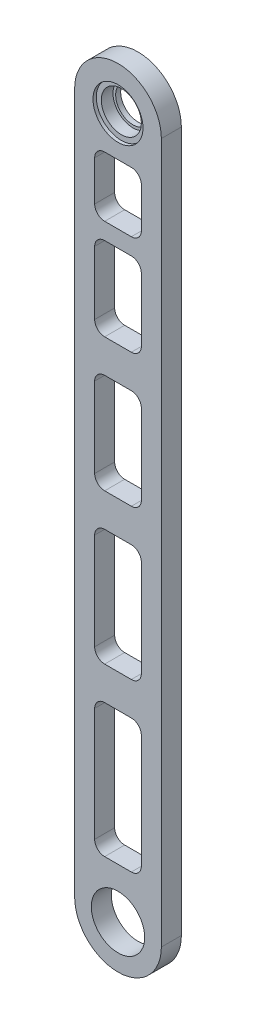
SolidWorks part; units mm, degrees
material "6061 合金"
ref_plane "前视基准面" through (0, 0, 0) normal (0, 0, 1) x (1, 0, 0)
ref_plane "上视基准面" through (0, 0, 0) normal (0, 1, 0) x (1, 0, 0)
ref_plane "右视基准面" through (0, 0, 0) normal (1, 0, 0) x (0, 0, -1)
sketch "草图1" plane through (0, 0, 0) normal (0, 0, 1) x (1, 0, 0)
  line L0 (0, 279.0477) -> (0, -66.8302) construction
  line L1 (-89.617, 0) -> (101.5542, 0) construction
  line L2 (-13, 0) -> (-13, 210)
  line L3 (13, 0) -> (13, 210)
  line L5 (-7.5, 240) -> (7.5, 240) construction
  line L6 (-7.5, 240) -> (-7.5, 220.6184) construction
  line L7 (-5.7625, 220.6184) -> (7.5, 220.6184) construction
  line L8 (7.5, 240) -> (7.5, 220.6184) construction
  circle A0 centre (0, 0) radius 8
  circle A1 centre (0, 210) radius 8
  arc A2 (-13, 0) -> (13, 0) centre (0, 0) ccw
  arc A3 (13, 210) -> (-13, 210) centre (0, 210) ccw
  arc A4 (7.5, 240) -> (-7.5, 240) centre (0, 240) ccw construction
  arc A5 (-13, 210) -> (-7.5, 220.6184) centre (0, 210) cw construction
  arc A6 (7.5, 220.6184) -> (13, 210) centre (0, 210) cw construction
  dimension "D1" = 16
  dimension "D2" = 210
  dimension "D3" = 16
  dimension "D4" = 5
  dimension "D5" = 5
  dimension "D6" = 15
  dimension "D7" = 30
extrude "凸台-拉伸1" add sketch "草图1" along normal blind 6
sketch "草图2" plane through (0, 0, 6) normal (0, 0, 1) x (1, 0, 0)
  line L0 (0, 0) -> (0, 269.7507) construction
  line L1 (13, 0) -> (13, 210) construction
  line L2 (-7, 175) -> (7, 175)
  line L3 (-7, 175) -> (-7, 150)
  line L4 (-7, 150) -> (7, 150)
  line L5 (7, 175) -> (7, 150)
  line L6 (-7, 175) -> (7, 150) construction
  line L7 (-7, 150) -> (7, 175) construction
  line L8 (-7, 140) -> (7, 140)
  line L9 (-7, 140) -> (-7, 110)
  line L10 (-7, 110) -> (7, 110)
  line L11 (7, 140) -> (7, 110)
  line L12 (-7, 140) -> (7, 110) construction
  line L13 (-7, 110) -> (7, 140) construction
  line L14 (-7, 100) -> (7, 100)
  line L15 (-7, 100) -> (-7, 65)
  line L16 (-7, 65) -> (7, 65)
  line L17 (7, 100) -> (7, 65)
  line L18 (-7, 100) -> (7, 65) construction
  line L19 (-7, 65) -> (7, 100) construction
  line L20 (-7, 55) -> (7, 55)
  line L21 (-7, 55) -> (-7, 15)
  line L22 (-7, 15) -> (7, 15)
  line L23 (7, 55) -> (7, 15)
  line L24 (-7, 55) -> (7, 15) construction
  line L25 (-7, 15) -> (7, 55) construction
  line L27 (-7, 198) -> (7, 198)
  line L28 (-7, 198) -> (-7, 180)
  line L29 (-7, 180) -> (7, 180)
  line L30 (7, 198) -> (7, 180)
  line L31 (-7, 198) -> (7, 180) construction
  line L32 (-7, 180) -> (7, 198) construction
  circle A0 centre (0, 0) radius 8 construction
  circle A1 centre (0, 210) radius 8 construction
  point P3 (0, 162.5)
  point P8 (0, 125)
  point P13 (0, 82.5)
  point P18 (0, 35)
  point P32 (0, 189)
  dimension "D1" = 6
  dimension "D2" = 15
  dimension "D3" = 40
  dimension "D4" = 10
  dimension "D5" = 35
  dimension "D6" = 10
  dimension "D7" = 30
  dimension "D8" = 10
  dimension "D9" = 25
  dimension "D10" = 5
  dimension "D11" = 12
extrude "切除-拉伸1" cut sketch "草图2" against normal through all
fillet "圆角1" radius 3 20 edges at (7, 198, 3) (-7, 198, 3) (7, 180, 3) (-7, 180, 3) (-7, 175, 3) (7, 175, 3) (7, 150, 3) (-7, 150, 3) (-7, 140, 3) (7, 140, 3) (7, 110, 3) (-7, 110, 3) (7, 100, 3) (-7, 100, 3) (7, 65, 3) (-7, 65, 3) (7, 15, 3) (-7, 15, 3) (-7, 55, 3) (7, 55, 3)
sketch "草图3" plane through (0, 0, 0) normal (0, 0, -1) x (-1, 0, 0)
  circle A0 centre (0, 210) radius 8
  circle A1 centre (0, 210) radius 5.2
  dimension "D1" = 10.4
extrude "凸台-拉伸2" add sketch "草图3" against normal up to surface (6 mm away) up to face at (0, 125, 6)
sketch "草图4" plane through (0, 0, 6) normal (0, 0, 1) x (1, 0, 0)
  circle A0 centre (0, 210) radius 6
  dimension "D1" = 12
extrude "切除-拉伸2" cut sketch "草图4" against normal blind 4.5
sketch "草图5" plane through (0, 0, 6) normal (0, 0, 1) x (1, 0, 0)
  circle A0 centre (0, 210) radius 7.5
  dimension "D1" = 15
extrude "切除-拉伸3" cut sketch "草图5" against normal blind 1
